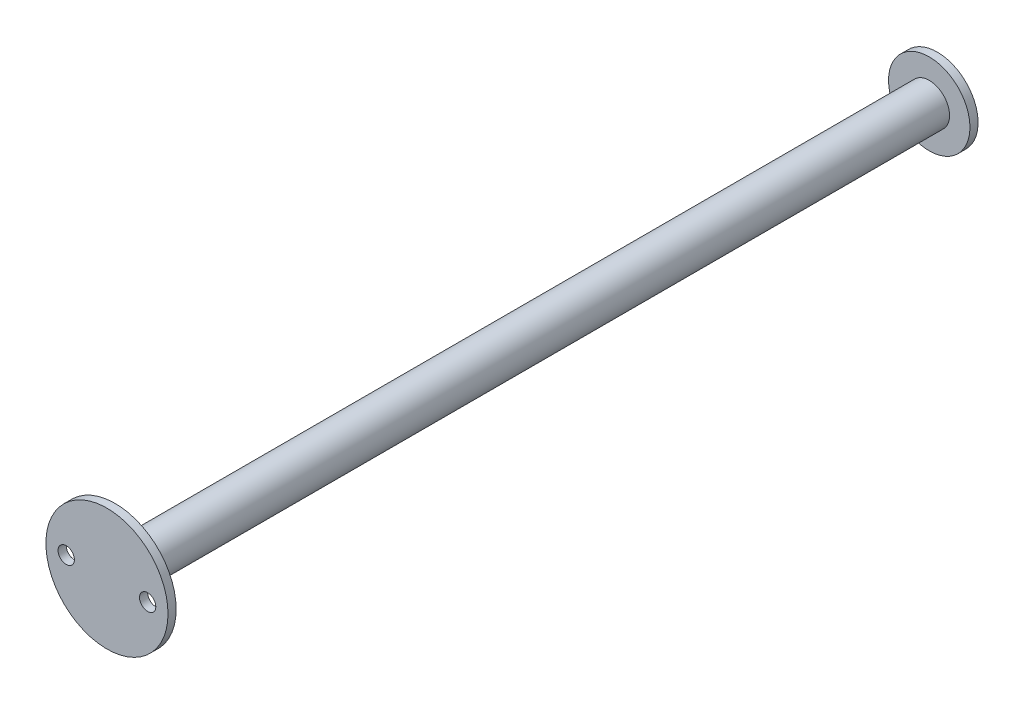
SolidWorks part; units mm, degrees
ref_plane "前视基准面" through (0, 0, 0) normal (0, 0, 1) x (1, 0, 0)
ref_plane "上视基准面" through (0, 0, 0) normal (0, 1, 0) x (1, 0, 0)
ref_plane "右视基准面" through (0, 0, 0) normal (1, 0, 0) x (0, 0, -1)
sketch "草图1" plane through (0, 0, 0) normal (0, 0, 1) x (1, 0, 0)
  circle A0 centre (0, 0) radius 5
  dimension "D1" = 10
extrude "凸台-拉伸1" add sketch "草图1" along normal mid plane 200
sketch "草图2" plane through (0, 0, -100) normal (0, 0, -1) x (-1, 0, 0)
  line L0 (-11.775, 0) -> (13.6329, 0) construction
  line L1 (0, 13.5089) -> (0, -14.1753) construction
  circle A0 centre (0, 0) radius 10
  dimension "D1" = 20
extrude "凸台-拉伸2" add sketch "草图2" along normal blind 2 contours A0
sketch "草图3" plane through (0, 0, 100) normal (0, 0, 1) x (1, 0, 0)
  line L0 (-20.273, 0) -> (24.5581, 0) construction
  line L1 (0, 20.8186) -> (0, -20.0078) construction
  circle A0 centre (0, 0) radius 15
  circle A1 centre (-10, 0) radius 2
  circle A2 centre (10, 0) radius 2
  dimension "D1" = 30
  dimension "D2" = 4
  dimension "D3" = 10
extrude "凸台-拉伸3" add sketch "草图3" along normal blind 2
